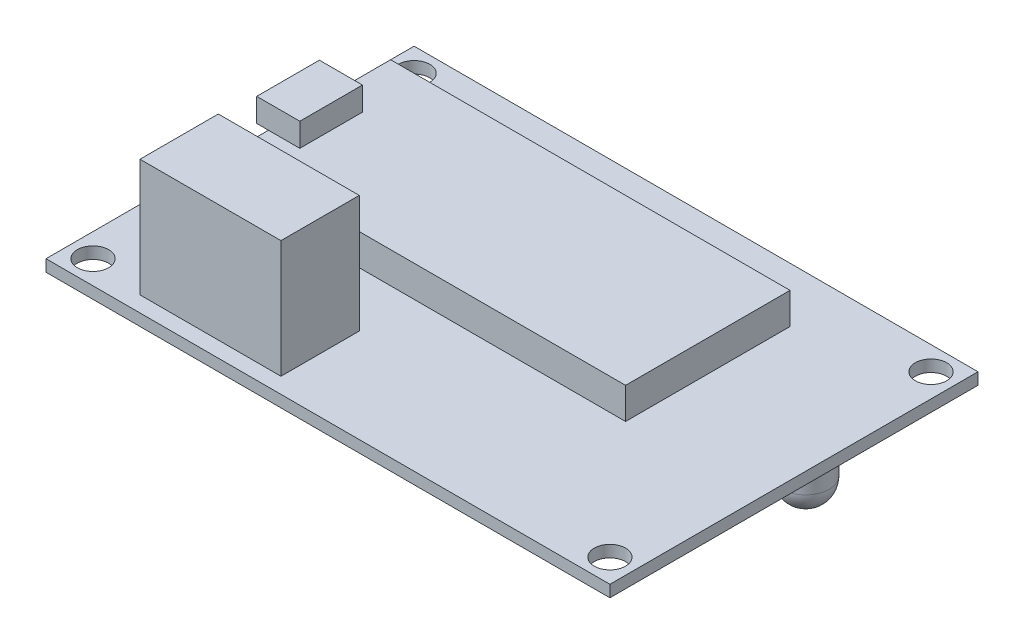
SolidWorks part; units mm, degrees
ref_plane "Front Plane" through (0, 0, 0) normal (0, 0, 1) x (1, 0, 0)
ref_plane "Top Plane" through (0, 0, 0) normal (0, 1, 0) x (1, 0, 0)
ref_plane "Right Plane" through (0, 0, 0) normal (1, 0, 0) x (0, 0, -1)
sketch "Sketch1" plane through (0, 0, 0) normal (0, 1, 0) x (1, 0, 0)
  line L1 (0, 0) -> (72, 0)
  line L2 (0, 0) -> (0, 47)
  line L3 (0, 47) -> (72, 47)
  line L4 (72, 0) -> (72, 47)
  dimension "D1" = 72
  dimension "D2" = 47
extrude "Boss-Extrude1" add sketch "Sketch1" along normal blind 1.5
sketch "Sketch2" plane through (0, 1.5, 0) normal (0, 1, 0) x (1, 0, 0)
  line L1 (72, 47) -> (0, 47) construction
  line L2 (3, 3) -> (69, 3)
  line L3 (3, 3) -> (3, 44)
  line L4 (3, 44) -> (69, 44)
  line L5 (69, 3) -> (69, 44)
  line L6 (0, 47) -> (0, 0) construction
  circle A0 centre (3, 3) radius 2
  circle A1 centre (69, 3) radius 2
  circle A2 centre (69, 44) radius 2
  circle A3 centre (3, 44) radius 2
  point P6 (36, 47)
  point P7 (36, 44)
  point P10 (0, 23.5)
  point P11 (3, 23.5)
  dimension "D3" = 4
  dimension "D1" = 66
  dimension "D2" = 41
extrude "Cut-Extrude1" cut sketch "Sketch2" against normal blind 1.5 contours L4 A2 L5 | L5 A2 L4 | L5 A1 L2 | L2 A1 L5 | L2 A0 L3 | L3 A0 L2 | L4 A3 L3 | L3 A3 L4
sketch "Sketch3" plane through (0, 1.5, 0) normal (0, 1, 0) x (1, 0, 0)
  line L1 (10, 2) -> (28, 2)
  line L2 (10, 2) -> (10, 12)
  line L3 (10, 12) -> (28, 12)
  line L4 (28, 2) -> (28, 12)
  dimension "D1" = 18
  dimension "D2" = 10
  dimension "D3" = 2
  dimension "D4" = 10
extrude "Boss-Extrude2" add sketch "Sketch3" along normal blind 15
sketch "Sketch4" plane through (0, 1.5, 0) normal (0, 1, 0) x (1, 0, 0)
  line L1 (4, 19) -> (55, 19)
  line L2 (4, 19) -> (4, 40)
  line L3 (4, 40) -> (55, 40)
  line L4 (55, 19) -> (55, 40)
  dimension "D1" = 51
  dimension "D2" = 21
  dimension "D3" = 4
  dimension "D4" = 7
extrude "Boss-Extrude3" add sketch "Sketch4" along normal blind 4
sketch "Sketch5" plane through (0, 5.5, 0) normal (0, 1, 0) x (1, 0, 0)
  line L1 (8, 32.4062) -> (2.5, 32.4062)
  line L2 (8, 32.4062) -> (8, 24.4062)
  line L3 (8, 24.4062) -> (2.5, 24.4062)
  line L4 (2.5, 32.4062) -> (2.5, 24.4062)
  dimension "D1" = 5.5
  dimension "D2" = 8
  dimension "D3" = 1.5
extrude "Boss-Extrude4" add sketch "Sketch5" along normal blind 3
sketch "Sketch6" plane through (0, 0, 0) normal (0, -1, 0) x (1, 0, 0)
  line L0 (72, -47) -> (0, -47) construction
  line L1 (72, 0) -> (72, -47) construction
  circle A0 centre (58, -39) radius 3
  dimension "D1" = 6
  dimension "D2" = 8
  dimension "D3" = 14
extrude "Boss-Extrude5" add sketch "Sketch6" along normal blind 16
fillet "Fillet1" radius 3 1 edges at (58, -16, -42)
